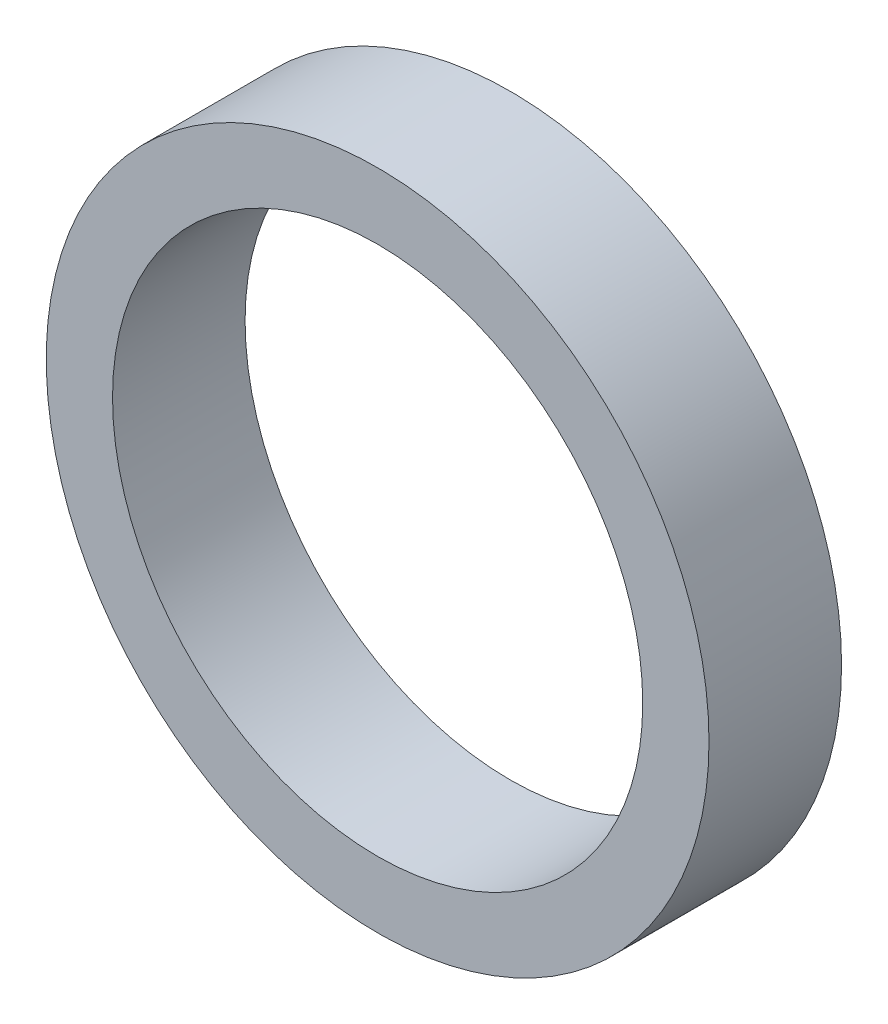
SolidWorks part; units mm, degrees
ref_plane "前基準面" through (0, 0, 0) normal (0, 0, 1) x (1, 0, 0)
ref_plane "上基準面" through (0, 0, 0) normal (0, 1, 0) x (1, 0, 0)
ref_plane "右基準面" through (0, 0, 0) normal (1, 0, 0) x (0, 0, -1)
sketch "草圖1" plane through (0, 0, 0) normal (0, 0, 1) x (1, 0, 0)
  circle A0 centre (0, 0) radius 500
  circle A1 centre (0, 0) radius 400
  dimension "D1" = 1000
  dimension "D2" = 800
extrude "填料-伸長1" add sketch "草圖1" along normal blind 200
